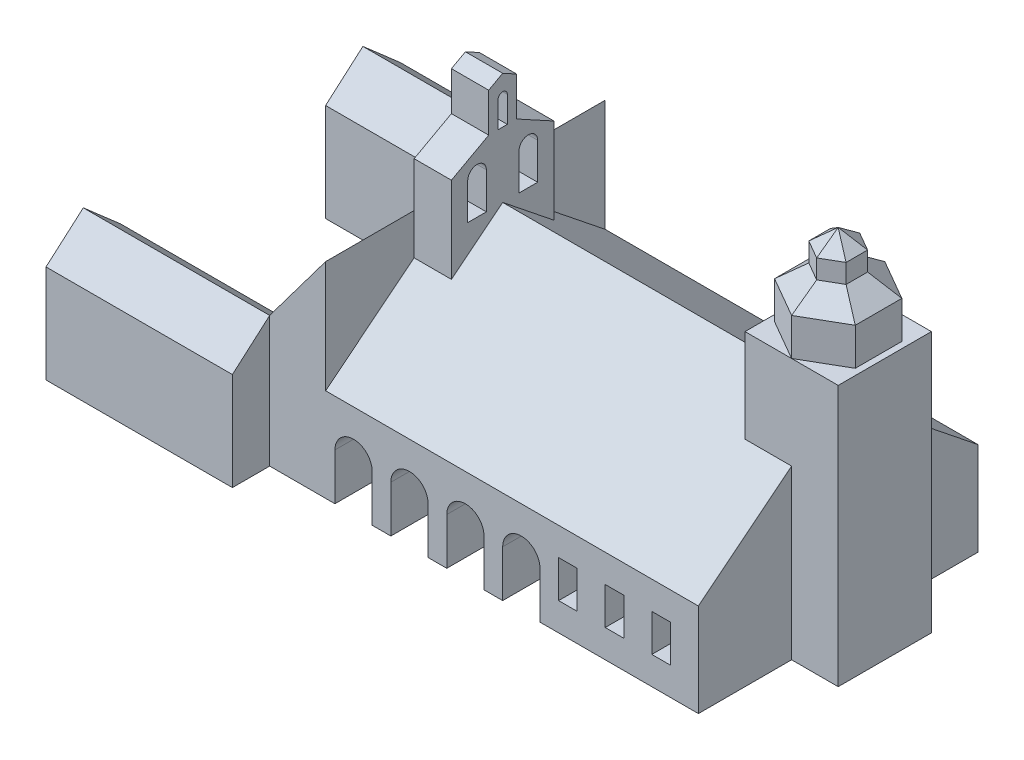
SolidWorks part; units mm, degrees
ref_plane "Alzado" through (0, 0, 0) normal (0, 0, 1) x (1, 0, 0)
ref_plane "Planta" through (0, 0, 0) normal (0, 1, 0) x (1, 0, 0)
ref_plane "Vista lateral" through (0, 0, 0) normal (1, 0, 0) x (0, 0, -1)
sketch "Croquis1" plane through (0, 0, 0) normal (0, 1, 0) x (1, 0, 0)
  line L1 (-10, -7.5) -> (10, -7.5)
  line L2 (-10, -7.5) -> (-10, 7.5)
  line L3 (-10, 7.5) -> (10, 7.5)
  line L4 (10, -7.5) -> (10, 7.5)
  line L5 (-10, -7.5) -> (10, 7.5) construction
  line L6 (-10, 7.5) -> (10, -7.5) construction
  point P0 (0, 0)
  dimension "D1" = 20
  dimension "D2" = 15
extrude "Saliente-Extruir1" add sketch "Croquis1" along normal blind 7
sketch "Croquis2" plane through (-10, 0, 0) normal (-1, 0, 0) x (0, 0, 1)
  line L0 (0, 7) -> (0, 13) construction
  line L1 (-7.5, 7) -> (0, 13)
  line L2 (0, 13) -> (7.5, 7)
  line L3 (7.5, 7) -> (-7.5, 7)
  line L4 (-7.5, 0) -> (7.5, 0)
  line L5 (7.5, 0) -> (7.5, 7)
  line L6 (7.5, 7) -> (-7.5, 7)
  line L7 (-7.5, 7) -> (-7.5, 0)
  line L8 (-7.5, 0) -> (7.5, 0) construction
  line L9 (7.5, 0) -> (7.5, 7) construction
  line L10 (7.5, 7) -> (-7.5, 7) construction
  line L11 (-7.5, 7) -> (-7.5, 0) construction
  dimension "D2" = 6
  dimension "D1" = 0
extrude "Saliente-Extruir2" add sketch "Croquis2" against normal up to surface (20 mm away) up to face at (10, 3.5, 0)
sketch "Croquis3" plane through (0, 0, 7.5) normal (0, 0, 1) x (1, 0, 0)
  line L0 (0, 0) -> (0, 7) construction
  line L1 (-10, 7) -> (10, 7) construction
  line L2 (0, 7) -> (10, 7) construction
  line L3 (2.5, 7) -> (2.5, 0) construction
  line L4 (-10, 0) -> (10, 0) construction
  line L5 (2.5, 3.5) -> (10, 3.5) construction
  line L6 (10, 7) -> (10, 0) construction
  line L8 (2.5, 3.5) -> (3.4993, 3.5)
  line L9 (2.5, 3.5) -> (2.5, 5.5)
  line L10 (2.5, 5.5) -> (3.4993, 5.5)
  line L11 (3.4993, 3.5) -> (3.4993, 5.5)
  line L12 (5, 3.5) -> (6, 3.5)
  line L13 (5, 3.5) -> (5, 5.5)
  line L14 (5, 5.5) -> (6, 5.5)
  line L15 (6, 3.5) -> (6, 5.5)
  line L16 (7.5, 3.5) -> (8.5, 3.5)
  line L17 (7.5, 3.5) -> (7.5, 5.5)
  line L18 (7.5, 5.5) -> (8.5, 5.5)
  line L19 (8.5, 3.5) -> (8.5, 5.5)
  point P5 (2.5, 7)
  point P8 (5, 7)
  point P9 (7.5, 7)
  dimension "D1" = 0.9993
  dimension "D2" = 1
  dimension "D3" = 1
  dimension "D4" = 2
  dimension "D5" = 2
  dimension "D6" = 2
extrude "Cortar-Extruir1" cut sketch "Croquis3" against normal blind 1
sketch "Croquis4" plane through (0, 0, 7.5) normal (0, 0, 1) x (1, 0, 0)
  line L0 (2.5, 5.5) -> (2.5, 8.1297) construction
  line L1 (2.5, 8.1297) -> (2.5, 0) construction
  line L2 (-10, 0) -> (10, 0) construction
  line L3 (2.5, 0) -> (1.5, 0) construction
  line L4 (-10, 0) -> (10, 0)
  line L5 (10, 0) -> (10, 7)
  line L6 (10, 7) -> (-10, 7)
  line L7 (-10, 7) -> (-10, 0)
  line L8 (-10, 0) -> (10, 0) construction
  line L9 (10, 0) -> (10, 7) construction
  line L10 (10, 7) -> (-10, 7) construction
  line L11 (-10, 7) -> (-10, 0) construction
  line L12 (1.5, 0) -> (-0.5, 0) construction
  line L13 (-0.5, 0) -> (-1.5, 0) construction
  line L14 (-1.5, 0) -> (-3.5, 0) construction
  line L15 (-3.5, 0) -> (-4.5, 0) construction
  line L16 (-4.5, 0) -> (-6.5, 0) construction
  line L17 (-6.5, 0) -> (-10, 0) construction
  line L18 (-6.5, 0) -> (-7.5, 0) construction
  line L19 (-7.5, 0) -> (-10, 0) construction
  line L20 (-7.5, 0) -> (-9.5, 0) construction
  line L21 (-10, 7) -> (-10, 5.5) construction
  line L22 (-10, 5.5) -> (2.5, 5.5) construction
  line L23 (-9.5, 0) -> (-9.5, 4.5)
  line L24 (-7.5, 0) -> (-7.5, 4.5)
  line L25 (-6.5, 0) -> (-6.5, 4.5)
  line L26 (-4.5, 0) -> (-4.5, 4.5)
  line L27 (-3.5, 0) -> (-3.5, 4.5)
  line L28 (-1.5, 0) -> (-1.5, 4.5)
  line L29 (-0.5, 0) -> (-0.5, 4.5)
  line L30 (1.5, 0) -> (1.5, 4.5)
  line L31 (-9.5, 0) -> (-7.5, 0)
  line L32 (-6.5, 0) -> (-4.5, 0)
  line L33 (-3.5, 0) -> (-1.5, 0)
  line L34 (-0.5, 0) -> (1.5, 0)
  arc A0 (-7.5, 4.5) -> (-9.5, 4.5) centre (-8.5, 4.5) ccw
  arc A1 (-4.5, 4.5) -> (-6.5, 4.5) centre (-5.5, 4.5) ccw
  arc A2 (-1.5, 4.5) -> (-3.5, 4.5) centre (-2.5, 4.5) ccw
  arc A3 (1.5, 4.5) -> (-0.5, 4.5) centre (0.5, 4.5) ccw
  dimension "D2" = 2
  dimension "D3" = 1
  dimension "D4" = 1
  dimension "D5" = 2
  dimension "D6" = 1
  dimension "D7" = 2
  dimension "D8" = 1
  dimension "D9" = 2
  dimension "D1" = 0
extrude "Cortar-Extruir2" cut sketch "Croquis4" against normal blind 2
sketch "Croquis6" plane through (0, 0, 7.5) normal (0, 0, 1) x (1, 0, 0)
  line L1 (10, 7) -> (10, 0) construction
  line L2 (-10, 0) -> (10, 0)
  line L3 (-10, 0) -> (-10, 2)
  line L4 (-10, 2) -> (10, 2)
  line L5 (10, 0) -> (10, 2)
  dimension "D1" = 2
extrude "Cortar-Extruir4" cut sketch "Croquis6" against normal blind 15
sketch "Croquis7" plane through (-10, 0, 0) normal (-1, 0, 0) x (0, 0, 1)
  line L0 (0, 13) -> (0, 2) construction
  line L1 (-7.5, 2) -> (7.5, 2) construction
mirror "Simetría1" about plane through (0, 0, 0) normal (0, 0, 1) of "Cortar-Extruir2", "Cortar-Extruir1"
ref_plane "Plano1" through (0, 2, 0) normal (0, -1, 0) x (-1, 0, 0)
sketch "Croquis9" plane through (0, 2, 0) normal (0, -1, 0) x (-1, 0, 0)
  line L0 (-10, 7.5) -> (10, 7.5) construction
  line L1 (10, 9.5) -> (13, 9.5)
  line L2 (10, 9.5) -> (10, -9.5)
  line L3 (10, -9.5) -> (13, -9.5)
  line L4 (13, 9.5) -> (13, -9.5)
  line L5 (10, -7.5) -> (-10, -7.5) construction
  dimension "D1" = 2
  dimension "D2" = 2
  dimension "D3" = 3
extrude "Saliente-Extruir3" add sketch "Croquis9" against normal blind 7
sketch "Croquis10" plane through (0, 0, 9.5) normal (0, 0, 1) x (1, 0, 0)
  line L0 (-13, 9) -> (-10, 13)
  line L1 (-10, 13) -> (-10, 9)
  line L2 (-10, 9) -> (-13, 9)
extrude "Saliente-Extruir4" add sketch "Croquis10" against normal blind 19
sketch "Croquis11" plane through (-10, 0, 0) normal (1, 0, 0) x (0, 0, -1)
  line L0 (2.75, 13) -> (-2.75, 13)
  line L1 (0, 13) -> (-9.5, 13) construction
  line L2 (-2.75, 13) -> (-2.75, 15.4088)
  line L3 (-2.75, 15.4088) -> (-0.75, 16.501)
  line L4 (-0.75, 16.501) -> (-0.75, 18.5904)
  line L5 (-0.75, 18.5904) -> (0, 19)
  line L6 (0, 19) -> (0.75, 18.5904)
  line L7 (0.75, 18.5904) -> (0.75, 16.501)
  line L8 (0.75, 16.501) -> (2.75, 15.4088)
  line L9 (2.75, 15.4088) -> (2.75, 13)
  line L10 (-0.75, 16.501) -> (0.75, 16.501) construction
  line L11 (-0.75, 18.5904) -> (0.75, 18.5904) construction
  line L12 (-2.75, 15.4088) -> (2.75, 15.4088) construction
  line L13 (-0.75, 16.501) -> (-0.75, 13) construction
  line L14 (0, 13) -> (0, 19) construction
  line L15 (0.75, 16.501) -> (0.75, 13) construction
  point P6 (0, 13)
  dimension "D1" = 2
  dimension "D2" = 2
  dimension "D3" = 6
  dimension "D4" = 1.5
extrude "Saliente-Extruir5" add sketch "Croquis11" along normal blind 2 separate body
sketch "Croquis12" plane through (0, 13, 0) normal (0, -1, 0) x (1, 0, 0)
  line L4 (-10, 2.75) -> (-10, -2.75)
  line L5 (-10, -2.75) -> (-8, -2.75)
  line L6 (-8, -2.75) -> (-8, 2.75)
  line L7 (-8, 2.75) -> (-10, 2.75)
  line L8 (-10, 2.75) -> (-10, -2.75)
  line L9 (-10, -2.75) -> (-8, -2.75)
  line L10 (-8, -2.75) -> (-8, 2.75)
  line L11 (-8, 2.75) -> (-10, 2.75)
  dimension "D1" = 0
extrude "Saliente-Extruir6" add sketch "Croquis12" along normal blind 3
sketch "Croquis13" plane through (-10, 0, 0) normal (-1, 0, 0) x (0, 0, 1)
  line L0 (0, 13) -> (0, 19) construction
  line L1 (-0.75, 16.501) -> (0.75, 16.501) construction
  line L2 (-0.75, 16.501) -> (-0.25, 16.501) construction
  line L3 (-0.25, 16.501) -> (0.25, 16.501) construction
  line L4 (0.25, 16.501) -> (0.75, 16.501) construction
  line L5 (-0.25, 16.501) -> (-0.25, 17.8947)
  line L6 (-0.25, 16.501) -> (0.25, 16.501)
  line L7 (0.25, 17.8947) -> (0.25, 16.501)
  line L8 (0, 13) -> (-2.75, 13) construction
  line L9 (0, 13) -> (2.75, 13) construction
  line L10 (-1.375, 13) -> (-1.375, 14.9524) construction
  line L11 (1.375, 13) -> (1.375, 14.9524) construction
  line L12 (-1.875, 13) -> (-0.875, 13)
  line L13 (0.875, 13) -> (1.875, 13)
  line L14 (-1.875, 13) -> (-1.875, 14.9524)
  line L15 (-0.875, 13) -> (-0.875, 14.9524)
  line L16 (0.875, 13) -> (0.875, 14.9524)
  line L17 (1.875, 13) -> (1.875, 14.9524)
  arc A0 (0.25, 17.8947) -> (-0.25, 17.8947) centre (0, 17.8947) ccw
  arc A1 (-0.875, 14.9524) -> (-1.875, 14.9524) centre (-1.375, 14.9524) ccw
  arc A2 (1.875, 14.9524) -> (0.875, 14.9524) centre (1.375, 14.9524) ccw
  point P24 (-1.375, 13)
  point P27 (1.375, 13)
  dimension "D1" = 0.5
  dimension "D2" = 0.5
  dimension "D3" = 1
  dimension "D4" = 1
extrude "Cortar-Extruir5" cut sketch "Croquis13" against normal blind 3
sketch "Croquis15" plane through (-10, 0, 0) normal (1, 0, 0) x (0, 0, -1)
  line L0 (-2.75, 13) -> (-9.5, 13) construction
  line L1 (-9.5, 2) -> (-7.5, 2)
  line L2 (-9.5, 2) -> (-9.5, 13)
  line L3 (-9.5, 13) -> (-7.5, 13)
  line L4 (-7.5, 2) -> (-7.5, 13)
  line L5 (9.5, 2) -> (7.5, 2) construction
  line L6 (9.5, 13) -> (7.5, 13)
  line L7 (9.5, 13) -> (9.5, 2)
  line L8 (9.5, 2) -> (7.5, 2)
  line L9 (7.5, 13) -> (7.5, 2)
extrude "Cortar-Extruir6" cut sketch "Croquis15" against normal blind 6
sketch "Croquis16" plane through (-13, 0, 0) normal (-1, 0, 0) x (0, 0, 1)
  line L0 (7.5, 9) -> (-7.5, 9) construction
  line L2 (-5.5, 2) -> (-5.5, 9)
  line L3 (-5.5, 9) -> (-9.5, 9)
  line L4 (-9.5, 2) -> (-9.5, 9)
  line L5 (-7.5, 2) -> (-9.5, 9) construction
  line L6 (-5.5, 9) -> (-7.5, 2) construction
  line L8 (9.5, 2) -> (9.5, 9)
  line L9 (9.5, 9) -> (5.5, 9)
  line L10 (5.5, 2) -> (5.5, 9)
  line L11 (7.5, 2) -> (5.5, 9) construction
  line L12 (9.5, 9) -> (7.5, 2) construction
  line L13 (-5.5, 2) -> (-9.5, 2)
  line L14 (5.5, 2) -> (9.5, 2)
  point P0 (-7.5, 2)
  point P6 (7.5, 2)
  dimension "D1" = 4
  dimension "D2" = 4
extrude "Saliente-Extruir7" add sketch "Croquis16" along normal blind 10
sketch "Croquis17" plane through (-23, 0, 0) normal (-1, 0, 0) x (0, 0, 1)
  line L0 (7.5, 9) -> (5.5, 7.2534)
  line L1 (5.5, 9) -> (5.5, 2) construction
  line L2 (5.5, 7.2534) -> (9.5, 7.2534)
  line L3 (9.5, 2) -> (9.5, 9) construction
  line L4 (9.5, 7.2534) -> (7.5, 9)
  line L5 (-7.5, 9) -> (-5.5, 7.2534)
  line L6 (-5.5, 9) -> (-9.5, 9) construction
  line L7 (-5.5, 2) -> (-5.5, 9) construction
  line L8 (-5.5, 7.2534) -> (-9.5, 7.2534)
  line L9 (-9.5, 9) -> (-9.5, 2) construction
  line L10 (-9.5, 7.2534) -> (-7.5, 9)
  line L11 (5.5, 9) -> (5.5, 2) construction
  line L12 (5.5, 2) -> (9.5, 2) construction
  line L13 (9.5, 9) -> (5.5, 9) construction
  line L14 (-9.5, 2) -> (-5.5, 2) construction
  line L15 (5.5, 9) -> (5.5, 2)
  line L16 (5.5, 2) -> (9.5, 2)
  line L17 (9.5, 2) -> (9.5, 9)
  line L18 (9.5, 9) -> (5.5, 9)
  line L19 (-9.5, 9) -> (-9.5, 2)
  line L20 (-9.5, 2) -> (-5.5, 2)
  line L21 (-5.5, 2) -> (-5.5, 9)
  line L22 (-5.5, 9) -> (-9.5, 9)
  line M4 (5.5, 9) -> (5.5, 2)
  line M6 (9.5, 2) -> (9.5, 9)
  line M7 (9.5, 9) -> (5.5, 9)
extrude "Cortar-Extruir7" cut sketch "Croquis17" against normal blind 10 contours L10 L22 L19 | L21 L22 L5 | L0 M7 M4 | L4 M6 M7
sketch "Croquis18" plane through (0, 2, 0) normal (0, -1, 0) x (-1, 0, 0)
  line L1 (-12.5, -2.5) -> (-7.5, -2.5)
  line L2 (-12.5, -2.5) -> (-12.5, 2.5)
  line L3 (-12.5, 2.5) -> (-7.5, 2.5)
  line L4 (-7.5, -2.5) -> (-7.5, 2.5)
  line L5 (-12.5, -2.5) -> (-7.5, 2.5) construction
  line L6 (-12.5, 2.5) -> (-7.5, -2.5) construction
  point P0 (-10, 0)
  dimension "D1" = 5
  dimension "D2" = 5
extrude "Saliente-Extruir8" add sketch "Croquis18" against normal blind 14
sketch "Croquis19" plane through (0, 16, 0) normal (0, 1, 0) x (1, 0, 0)
  line L1 (10, 2.5) -> (7.8349, 1.25)
  line L2 (7.8349, 1.25) -> (7.8349, -1.25)
  line L3 (7.8349, -1.25) -> (10, -2.5)
  line L4 (10, -2.5) -> (12.1651, -1.25)
  line L5 (12.1651, -1.25) -> (12.1651, 1.25)
  line L6 (12.1651, 1.25) -> (10, 2.5)
  circle A0 centre (10, 0) radius 2.1651 construction
extrude "Saliente-Extruir9" add sketch "Croquis19" along normal blind 2
sketch "Croquis20" plane through (0, 18, 0) normal (0, 1, 0) x (1, 0, 0)
  line L0 (10, 1.1547) -> (10, 1) construction
  line L1 (10, 1.1547) -> (9, 0.5774)
  line L2 (9, 0.5774) -> (9, -0.5774)
  line L3 (9, -0.5774) -> (10, -1.1547)
  line L4 (10, -1.1547) -> (11, -0.5774)
  line L5 (11, -0.5774) -> (11, 0.5774)
  line L6 (11, 0.5774) -> (10, 1.1547)
  line L8 (10, -1) -> (10, -1.1547) construction
  circle A0 centre (10, 0) radius 1 construction
  point P15 (10, 0)
  dimension "D1" = 2
extrude "Saliente-Extruir10" add sketch "Croquis20" along normal blind 2
sketch "Croquis21" plane through (0, 18, 0) normal (0, 1, 0) x (1, 0, 0)
  line L6 (12.1651, 1.25) -> (10, 2.5)
  line L7 (10, 2.5) -> (7.8349, 1.25)
  line L8 (7.8349, 1.25) -> (7.8349, -1.25)
  line L9 (7.8349, -1.25) -> (10, -2.5)
  line L10 (10, -2.5) -> (12.1651, -1.25)
  line L11 (12.1651, -1.25) -> (12.1651, 1.25)
  line L12 (12.1651, 1.25) -> (10, 2.5)
  line L13 (10, 2.5) -> (7.8349, 1.25)
  line L14 (7.8349, 1.25) -> (7.8349, -1.25)
  line L15 (7.8349, -1.25) -> (10, -2.5)
  line L16 (10, -2.5) -> (12.1651, -1.25)
  line L17 (12.1651, -1.25) -> (12.1651, 1.25)
  dimension "D1" = 0
extrude "Saliente-Extruir11" add sketch "Croquis21" along normal blind 3 draft 50
sketch "Croquis22" plane through (0, 20, 0) normal (0, 1, 0) x (1, 0, 0)
  line L6 (11, 0.5774) -> (10, 1.1547)
  line L7 (10, 1.1547) -> (9, 0.5774)
  line L8 (9, 0.5774) -> (9, -0.5774)
  line L9 (9, -0.5774) -> (10, -1.1547)
  line L10 (10, -1.1547) -> (11, -0.5774)
  line L11 (11, -0.5774) -> (11, 0.5774)
  line L12 (11, 0.5774) -> (10, 1.1547)
  line L13 (10, 1.1547) -> (9, 0.5774)
  line L14 (9, 0.5774) -> (9, -0.5774)
  line L15 (9, -0.5774) -> (10, -1.1547)
  line L16 (10, -1.1547) -> (11, -0.5774)
  line L17 (11, -0.5774) -> (11, 0.5774)
  dimension "D1" = 0
extrude "Saliente-Extruir12" add sketch "Croquis22" along normal blind 3 draft 50
sketch "Croquis23" plane through (-13, 0, 0) normal (-1, 0, 0) x (0, 0, 1)
  line L0 (-5.5, 7.2534) -> (5.5, 7.2534) construction
  line L1 (0, 7.2534) -> (0, 2) construction
  line L2 (-2, 5.2534) -> (-2, 2)
  line L3 (-10.45, 2) -> (10.45, 2) construction
  line L4 (-2, 2) -> (2.0457, 2)
  line L5 (2.0457, 2) -> (2, 5.2534)
  line L6 (-2, 5.2534) -> (2, 5.2534) construction
  line L7 (-6.5, 8.1267) -> (6.5, 8.1267) construction
  line L8 (-1.5, 7.6267) -> (-2.5, 7.6267)
  line L9 (-1.5, 7.6267) -> (-1.5, 8.6267)
  line L10 (-1.5, 8.6267) -> (-2.5, 8.6267)
  line L11 (-2.5, 7.6267) -> (-2.5, 8.6267)
  line L12 (-1.5, 7.6267) -> (-2.5, 8.6267) construction
  line L13 (-1.5, 8.6267) -> (-2.5, 7.6267) construction
  line L14 (1.5, 7.6267) -> (2.5, 7.6267)
  line L15 (1.5, 7.6267) -> (1.5, 8.6267)
  line L16 (1.5, 8.6267) -> (2.5, 8.6267)
  line L17 (2.5, 7.6267) -> (2.5, 8.6267)
  line L18 (1.5, 7.6267) -> (2.5, 8.6267) construction
  line L19 (1.5, 8.6267) -> (2.5, 7.6267) construction
  line L20 (-7.5, 9) -> (-5.5, 7.2534) construction
  line L21 (7.5, 9) -> (5.5, 7.2534) construction
  arc A0 (2, 5.2534) -> (-2, 5.2534) centre (0, 5.2534) ccw
  point P13 (2, 8.1267)
  point P15 (-2, 8.1267)
  point P30 (1.9543, 8.1267)
  point P31 (-2, 8.1267)
  point P32 (2, 8.1267)
  point P33 (2, 8.1267)
  dimension "D1" = 4
  dimension "D2" = 1
  dimension "D3" = 1
  dimension "D4" = 1
  dimension "D5" = 1
extrude "Cortar-Extruir8" cut sketch "Croquis23" against normal blind 1
sketch "Croquis24" plane through (-12, 0, 0) normal (-1, 0, 0) x (0, 0, 1)
  line L3 (-2, 5.2534) -> (-2, 2)
  line L4 (-2, 2) -> (2.0457, 2)
  line L5 (2.0457, 2) -> (2, 5.2534)
  line L6 (-2, 5.2534) -> (-2, 2)
  line L7 (-2, 2) -> (2.0457, 2)
  line L8 (2.0457, 2) -> (2, 5.2534)
  arc A1 (2, 5.2534) -> (-2, 5.2534) centre (0, 5.2534) ccw
  arc A2 (2, 5.2534) -> (-2, 5.2534) centre (0, 5.2534) ccw
  dimension "D1" = 0
extrude "Cortar-Extruir9" cut sketch "Croquis24" against normal blind 3
sketch "Croquis25" plane through (0, 2, 0) normal (0, -1, 0) x (1, 0, 0)
  circle A0 centre (0, 0) radius 1.575
  dimension "D1" = 3.15
extrude "Cortar-Extruir10" cut sketch "Croquis25" against normal blind 2.5
